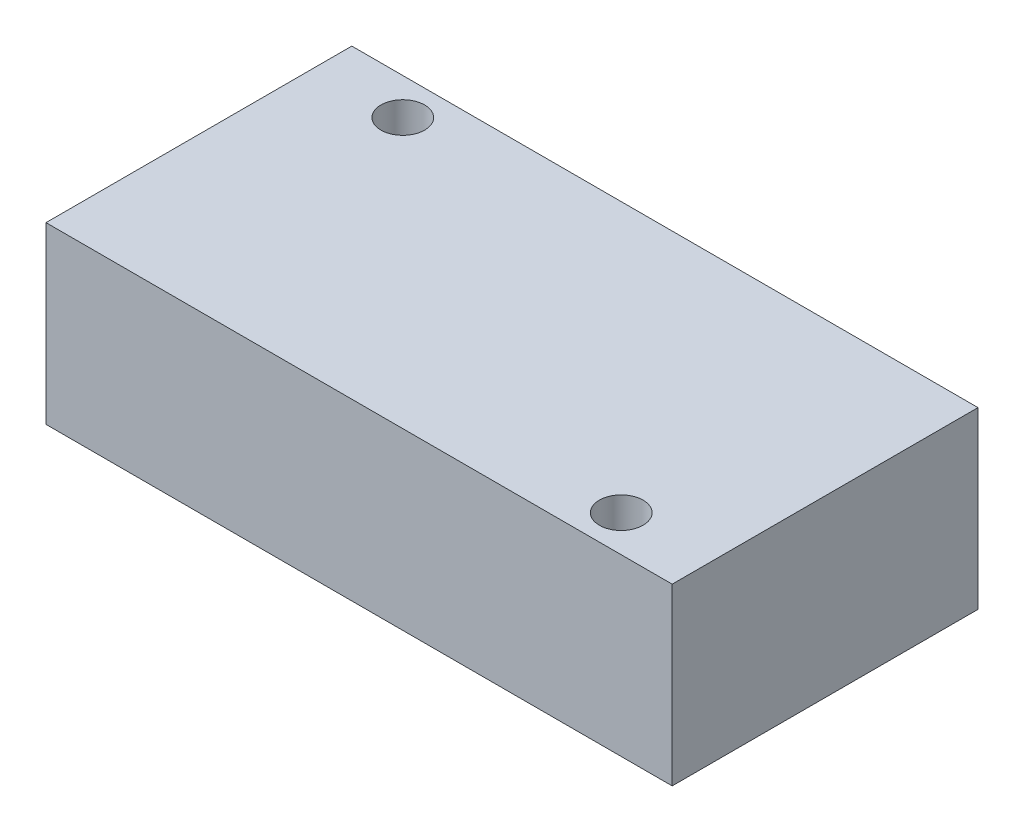
SolidWorks part; units mm, degrees
material "ABS"
ref_plane "前基準面" through (0, 0, 0) normal (0, 0, 1) x (1, 0, 0)
ref_plane "上基準面" through (0, 0, 0) normal (0, 1, 0) x (1, 0, 0)
ref_plane "右基準面" through (0, 0, 0) normal (1, 0, 0) x (0, 0, -1)
sketch "草圖1" plane through (0, 0, 0) normal (0, 1, 0) x (1, 0, 0)
  line L0 (0, 0) -> (0, 15.8213) construction
  line L1 (-21.5, -10.5) -> (21.5, -10.5)
  line L2 (-21.5, -10.5) -> (-21.5, 10.5)
  line L3 (-21.5, 10.5) -> (21.5, 10.5)
  line L4 (21.5, -10.5) -> (21.5, 10.5)
  line L5 (-21.5, -10.5) -> (21.5, 10.5) construction
  line L6 (-21.5, 10.5) -> (21.5, -10.5) construction
  line L7 (0, 0) -> (-27.5221, 0) construction
  circle A0 centre (-15.5, 8) radius 1.5
  circle A2 centre (15.5, -8) radius 1.5
  point P0 (0, 0)
  dimension "D5" = 3
  dimension "D1" = 43
  dimension "D2" = 21
  dimension "D3" = 2.5
  dimension "D4" = 6
  dimension "D6" = 6
  dimension "D7" = 2.5
extrude "填料-伸長1" add sketch "草圖1" along normal blind 12
